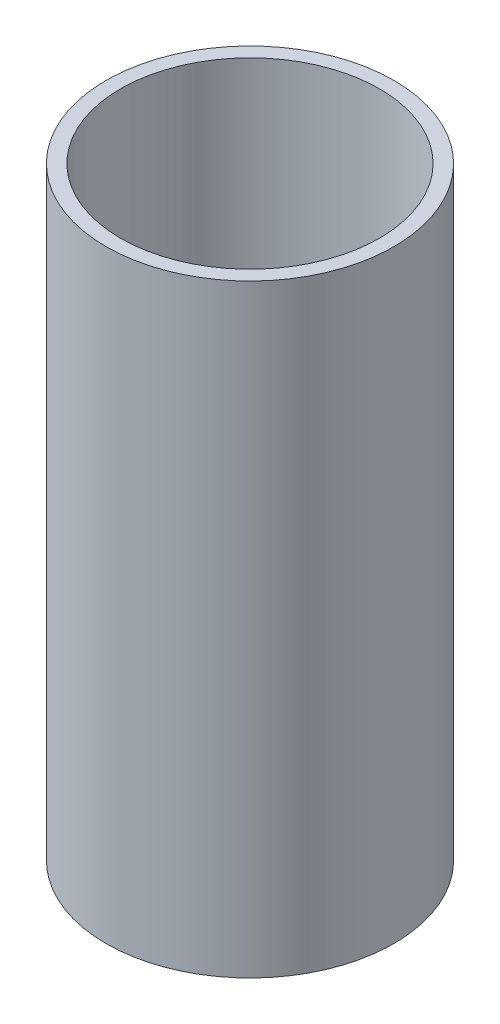
SolidWorks part; units mm, degrees
ref_plane "Front Plane" through (0, 0, 0) normal (0, 0, 1) x (1, 0, 0)
ref_plane "Top Plane" through (0, 0, 0) normal (0, 1, 0) x (1, 0, 0)
ref_plane "Right Plane" through (0, 0, 0) normal (1, 0, 0) x (0, 0, -1)
sketch "Sketch1" plane through (0, 0, 0) normal (0, 1, 0) x (1, 0, 0)
  circle A0 centre (0, 0) radius 11.925
  circle A1 centre (0, 0) radius 9.525
  dimension "D1" = 23.85
  dimension "D2" = 19.05
extrude "Boss-Extrude1" add sketch "Sketch1" along normal blind 50
sketch "Sketch2" plane through (0, 0, 0) normal (0, -1, 0) x (1, 0, 0)
  circle A0 centre (0, 0) radius 10.8
  dimension "D1" = 21.6
extrude "Cut-Extrude1" cut sketch "Sketch2" against normal blind 20
sketch "Sketch3" plane through (0, 50, 0) normal (0, 1, 0) x (1, 0, 0)
  circle A0 centre (0, 0) radius 10.725
  dimension "D1" = 21.45
extrude "Cut-Extrude2" cut sketch "Sketch3" against normal blind 20
